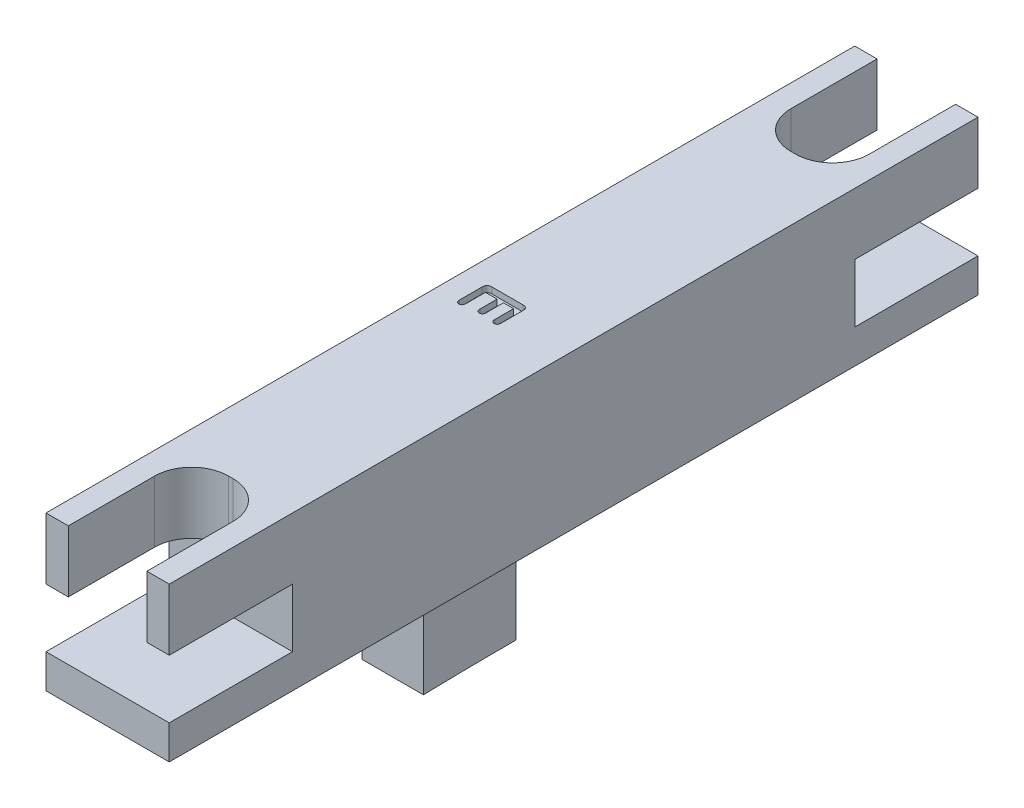
SolidWorks part; units mm, degrees
ref_plane "Front Plane" through (0, 0, 0) normal (0, 0, 1) x (1, 0, 0)
ref_plane "Top Plane" through (0, 0, 0) normal (0, 1, 0) x (1, 0, 0)
ref_plane "Right Plane" through (0, 0, 0) normal (1, 0, 0) x (0, 0, -1)
sketch "Sketch2" plane through (0, 0, 0) normal (0, 1, 0) x (1, 0, 0)
  line L1 (0, 0) -> (10.16, 0)
  line L2 (0, 0) -> (0, 66.675)
  line L3 (0, 66.675) -> (10.16, 66.675)
  line L4 (10.16, 0) -> (10.16, 66.675)
  dimension "D1" = 66.675
  dimension "D2" = 10.16
extrude "Boss-Extrude1" add sketch "Sketch2" along normal blind 12.7
sketch "Sketch3" plane through (0, 0, 0) normal (0, -1, 0) x (1, 0, 0)
  line L0 (10.16, -66.675) -> (0, -66.675) construction
  line L1 (0, 0) -> (5.08, 0)
  line L2 (0, 0) -> (0, -66.675)
  line L3 (0, -66.675) -> (5.08, -66.675)
  line L4 (5.08, 0) -> (5.08, -66.675)
  line L5 (0, -66.675) -> (0, 0) construction
  line L6 (0, 0) -> (10.16, 0) construction
  line L7 (-16.0623, -37.465) -> (21.3262, -37.465) construction
  line L8 (-9.1988, -29.21) -> (67.1361, -29.21) construction
  line L9 (0, -37.465) -> (0, -29.21) construction
  line L10 (-21.0326, -20.955) -> (28.4478, -20.955) construction
  line L11 (2.54, 0) -> (2.54, -66.675) construction
  line L12 (-27.1779, -45.72) -> (27.7068, -45.72) construction
  line L13 (5.08, -33.655) -> (0, -33.655)
  line L14 (5.08, -48.895) -> (0, -48.895)
  line L15 (5.08, -48.895) -> (5.08, -42.545) construction
  line L16 (5.08, -42.545) -> (0, -42.545)
  line L17 (0, -48.895) -> (0, -42.545) construction
  line L18 (5.08, -48.895) -> (0, -42.545) construction
  line L19 (5.08, -42.545) -> (0, -48.895) construction
  line L20 (5.08, -40.64) -> (0, -40.64)
  line L21 (5.08, -40.64) -> (5.08, -34.29)
  line L22 (5.08, -34.29) -> (0, -34.29)
  line L23 (0, -40.64) -> (0, -34.29)
  line L24 (5.08, -40.64) -> (0, -34.29) construction
  line L25 (5.08, -34.29) -> (0, -40.64) construction
  line L26 (5.08, -32.385) -> (0, -32.385)
  line L27 (5.08, -32.385) -> (5.08, -26.035)
  line L28 (5.08, -26.035) -> (0, -26.035)
  line L29 (0, -32.385) -> (0, -26.035)
  line L30 (5.08, -32.385) -> (0, -26.035) construction
  line L31 (5.08, -26.035) -> (0, -32.385) construction
  line L32 (5.08, -24.13) -> (0, -24.13)
  line L33 (5.08, -24.13) -> (5.08, -17.78)
  line L34 (5.08, -17.78) -> (0, -17.78)
  line L35 (0, -24.13) -> (0, -17.78)
  line L36 (5.08, -24.13) -> (0, -17.78) construction
  line L37 (5.08, -17.78) -> (0, -24.13) construction
  point P16 (0, -33.3375)
  point P17 (0, -33.3375)
  point P24 (2.54, -45.72)
  point P29 (2.54, -29.21)
  point P30 (2.54, -37.465)
  point P41 (2.54, -20.955)
  dimension "D1" = 5.08
  dimension "D2" = 0
  dimension "D3" = 8.255
  dimension "D4" = 8.255
  dimension "D5" = 8.255
  dimension "D6" = 5.08
  dimension "D7" = 6.35
  dimension "D8" = 6.35
  dimension "D9" = 6.35
  dimension "D10" = 6.35
  dimension "D11" = 1.27
extrude "Boss-Extrude2" add sketch "Sketch3" along normal blind 12.7 contours L4 L28 L2 L26 | L4 L26 L2 L13
sketch "Sketch4" plane through (0, 0, 0) normal (0, 0, 1) x (1, 0, 0)
  line L0 (0, 12.7) -> (10.16, 12.7) construction
  line L1 (0, 7.62) -> (1.8415, 7.62)
  line L2 (0, 7.62) -> (0, 2.794)
  line L3 (0, 2.794) -> (10.16, 2.794)
  line L4 (10.16, 7.62) -> (10.16, 2.794)
  line L5 (1.8415, 12.7) -> (8.3185, 12.7)
  line L6 (1.8415, 12.7) -> (1.8415, 7.62)
  line L8 (8.3185, 12.7) -> (8.3185, 7.62)
  line L9 (8.3185, 7.62) -> (10.16, 7.62)
  line L10 (10.16, 12.7) -> (10.16, 0) construction
  line L11 (0, 12.7) -> (0, 0) construction
  point P10 (5.08, 12.7)
  dimension "D2" = 6.477
  dimension "D3" = 4.826
  dimension "D4" = 5.08
extrude "Cut-Extrude1" cut sketch "Sketch4" against normal blind 10.16
ref_plane "Plane1" through (0, 0, -33.3375) normal (0, 0, 1) x (1, 0, 0)
fillet "Fillet2" radius 3.048 2 edges at (8.3185, 10.16, -10.16) (1.8415, 10.16, -10.16)
mirror "Mirror1" about plane through (0, 0, -33.3375) normal (0, 0, 1) of "Fillet2", "Cut-Extrude1"
sketch "Sketch5" plane through (0, 0, 0) normal (-1, 0, 0) x (0, 0, 1)
  line L0 (-33.3375, -10.668) -> (-33.3375, -12.7) construction
  line L2 (-66.675, -12.7) -> (0, -12.7)
  line L3 (-66.675, -12.7) -> (-66.675, 0) construction
  line L4 (-26.035, -12.7) -> (-33.655, -12.7) construction
  line L5 (0, -12.7) -> (0, 0) construction
  arc A0 (-66.675, -12.7) -> (0, -12.7) centre (-33.3375, -285.1557) cw
  dimension "D1" = 2.032
  dimension "D2" = 12.7
extrude "Cut-Extrude4" cut sketch "Sketch5" against normal through all
fillet "Fillet1" [suppressed] radius 2.54
sketch "Sketch6" plane through (0, 12.7, 0) normal (0, 1, 0) x (1, 0, 0)
  line L0 (1.8415, 7.112) -> (1.8415, 59.563) construction
  arc A0 (4.8895, 10.16) -> (1.8415, 7.112) centre (4.8895, 7.112) ccw construction
  text T0 "E\r\n" font "Arial Rounded MT Bold" height 3.5
extrude "Cut-Extrude5" cut sketch "Sketch6" against normal blind 0.508
